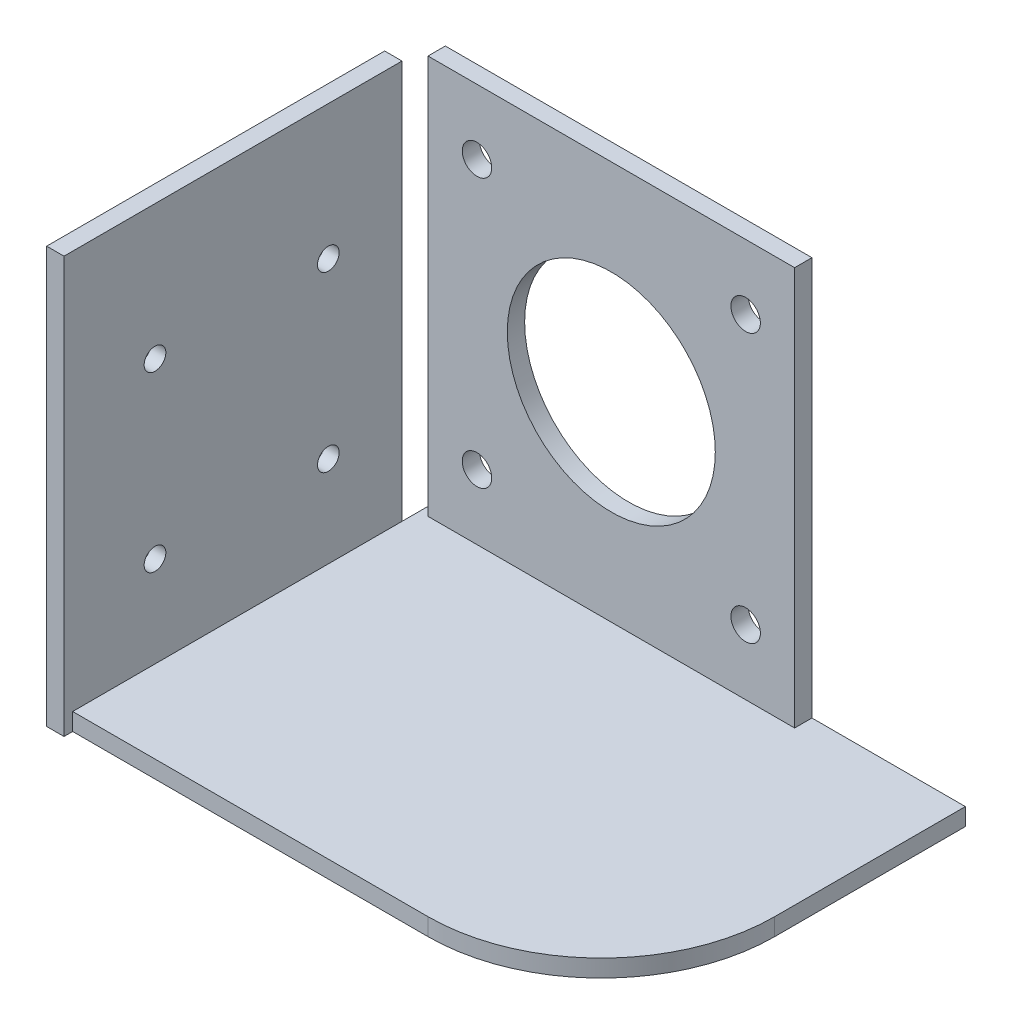
SolidWorks part; units mm, degrees
ref_plane "Front Plane" through (0, 0, 0) normal (0, 0, 1) x (1, 0, 0)
ref_plane "Top Plane" through (0, 0, 0) normal (0, 1, 0) x (1, 0, 0)
ref_plane "Right Plane" through (0, 0, 0) normal (1, 0, 0) x (0, 0, -1)
sketch "Sketch1" plane through (0, 0, 0) normal (0, 0, 1) x (1, 0, 0)
  line L1 (-21.15, -23) -> (21.15, -23)
  line L2 (-21.15, -23) -> (-21.15, 23)
  line L3 (-21.15, 23) -> (21.15, 23)
  line L4 (21.15, -23) -> (21.15, 23)
  line L5 (-21.15, -23) -> (21.15, 23) construction
  line L6 (-21.15, 23) -> (21.15, -23) construction
  circle A0 centre (0, 0) radius 12
  circle A1 centre (-15.5, 15.5) radius 1.7
  circle A2 centre (15.5, 15.5) radius 1.7
  circle A3 centre (15.5, -15.5) radius 1.7
  circle A4 centre (-15.5, -15.5) radius 1.7
  point P0 (0, 0)
  point P19 (-0.2272, 1.6228)
  point P20 (0, 0)
  dimension "D3" = 24
  dimension "D4" = 3.4
  dimension "D8" = 31
  dimension "D6" = 7.5
  dimension "D1" = 42.3
  dimension "D2" = 46
  dimension "D5" = 5.65
  dimension "D7" = 4
extrude "Boss-Extrude1" add sketch "Sketch1" along normal blind 2 contours L3 L4 L1 L2
sketch "Sketch4" plane through (0, -23, 0) normal (0, -1, 0) x (1, 0, 0)
  line L1 (-21.15, 0) -> (38.85, 0)
  line L3 (-21.15, 42) -> (18.85, 42)
  line L4 (38.85, 0) -> (38.85, 22)
  line L5 (-21.15, 0) -> (-22.15, 0)
  line L7 (-21.15, 42) -> (-22.15, 42)
  line L8 (-22.15, 0) -> (-22.15, 42)
  arc A0 (38.85, 22) -> (18.85, 42) centre (18.85, 22) ccw
  point P9 (38.85, 42)
  dimension "D3" = 20
  dimension "D1" = 60
  dimension "D2" = 42
  dimension "D4" = 1
extrude "Boss-Extrude4" add sketch "Sketch4" along normal blind 2
sketch "Sketch6" plane through (0, 23, 0) normal (0, 1, 0) x (1, 0, 0)
  line L3 (-22.15, -42) -> (-22.15, 0) construction
  line L4 (-22.15, -4) -> (-24.15, -4)
  line L5 (-22.15, -4) -> (-22.15, -43)
  line L7 (-22.15, -43) -> (-24.15, -43)
  line L9 (-24.15, -4) -> (-24.15, -43)
  line L10 (21.15, -2) -> (-21.15, -2) construction
  dimension "D1" = 2
  dimension "D2" = 2
  dimension "D3" = 39
extrude "Boss-Extrude6" add sketch "Sketch6" against normal up to surface (48 mm away) up to face at (11.2784, -25, 22.0284)
sketch "Sketch10" plane through (-24.15, 0, 0) normal (-1, 0, 0) x (0, 0, 1)
  line L1 (4, 23) -> (43, 23) construction
  point P7 (22.5, 0)
  point P8 (12.5, 7.5)
  point P9 (32.5, 7.5)
  point P10 (12.5, -12.5)
  point P11 (32.5, -12.5)
  dimension "D1" = 15.5
  dimension "D2" = 15.5
  dimension "D4" = 10
  dimension "D5" = 10
  dimension "D6" = 20
  dimension "D7" = 20
  dimension "D8" = 10
  dimension "D9" = 10
hole_wizard "M3 Tapped Hole2" positions "3DSketch2" profile "Sketch11" tap size "M3" standard "ISO" end condition up to next
sketch3d "3DSketch2"
  point P0 (-24.15, 7.5, 12.5)
  point P3 (-24.15, 7.5, 32.5)
  point P6 (-24.15, -12.5, 32.5)
  point P9 (-24.15, -12.5, 12.5)
sketch "Sketch11" plane through (-24.15, 7.5, 12.5) normal (0, 1, 0) x (0, 0, 1)
  line L0 (0, 0) -> (0, 2)
  line L1 (0, 2) -> (1.25, 2)
  line L2 (1.25, 2) -> (1.25, 0.275)
  line L3 (1.25, 0.275) -> (1.525, 0)
  line L5 (1.525, 0) -> (0, 0)
  line L6 (-1.25, 0.275) -> (-1.525, 0) construction
  line L11 (0, -6.35) -> (0, 107.95) construction
  dimension "Thru Tap Drill Dia." = 2.5
  dimension "Thru Tap Drill Depth" = 2
  dimension "Near C'Sink Dia." = 3.05
  dimension "Near C'Sink Angle" = 90
cosmetic thread "Hole Thread1" parameters "D1"=2, "D2"=3
cosmetic thread "Hole Thread2" parameters "D1"=2, "D2"=3
cosmetic thread "Hole Thread3" parameters "D1"=2, "D2"=3
cosmetic thread "Hole Thread4" parameters "D1"=2, "D2"=3
